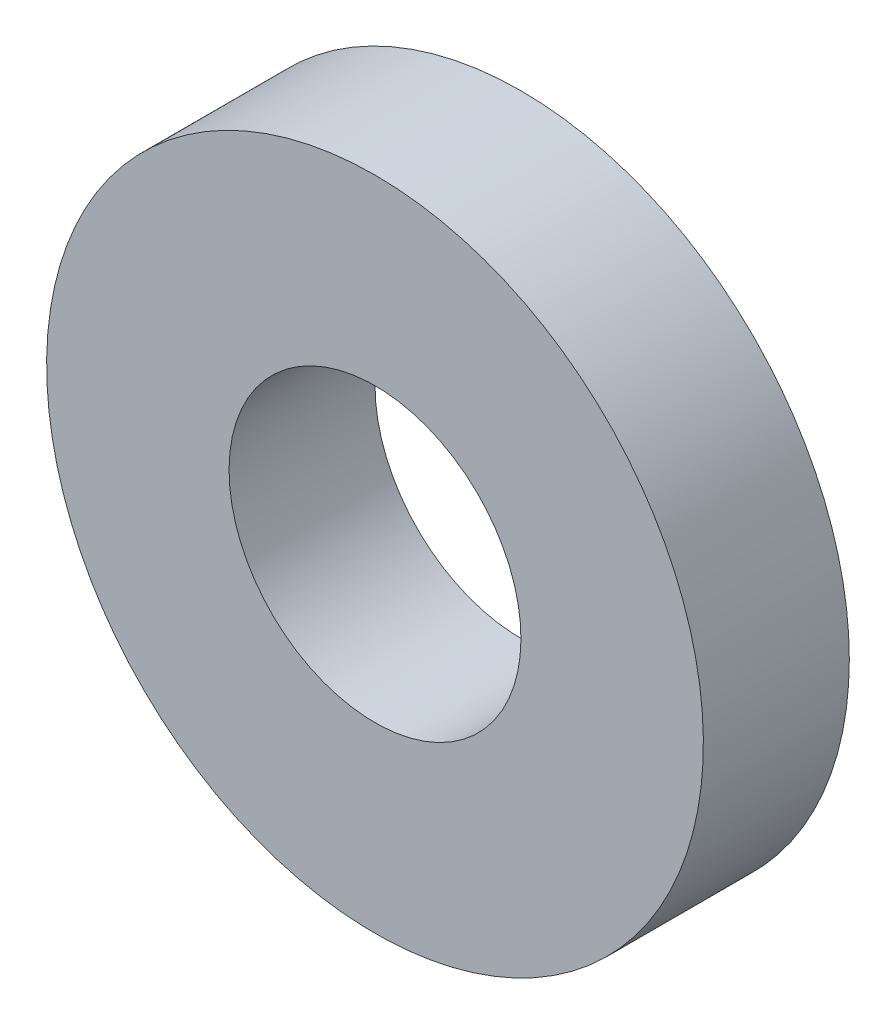
SolidWorks part; units mm, degrees
ref_plane "Front Plane" through (0, 0, 0) normal (0, 0, 1) x (1, 0, 0)
ref_plane "Top Plane" through (0, 0, 0) normal (0, 1, 0) x (1, 0, 0)
ref_plane "Right Plane" through (0, 0, 0) normal (1, 0, 0) x (0, 0, -1)
sketch "Sketch1" plane through (0, 0, 0) normal (0, 0, 1) x (1, 0, 0)
  circle A0 centre (0, 0) radius 4
  circle A1 centre (0, 0) radius 4 construction
  circle A2 centre (0, 0) radius 9
  dimension "D1" = 5
extrude "Boss-Extrude1" add sketch "Sketch1" along normal up to surface (4 mm away)
